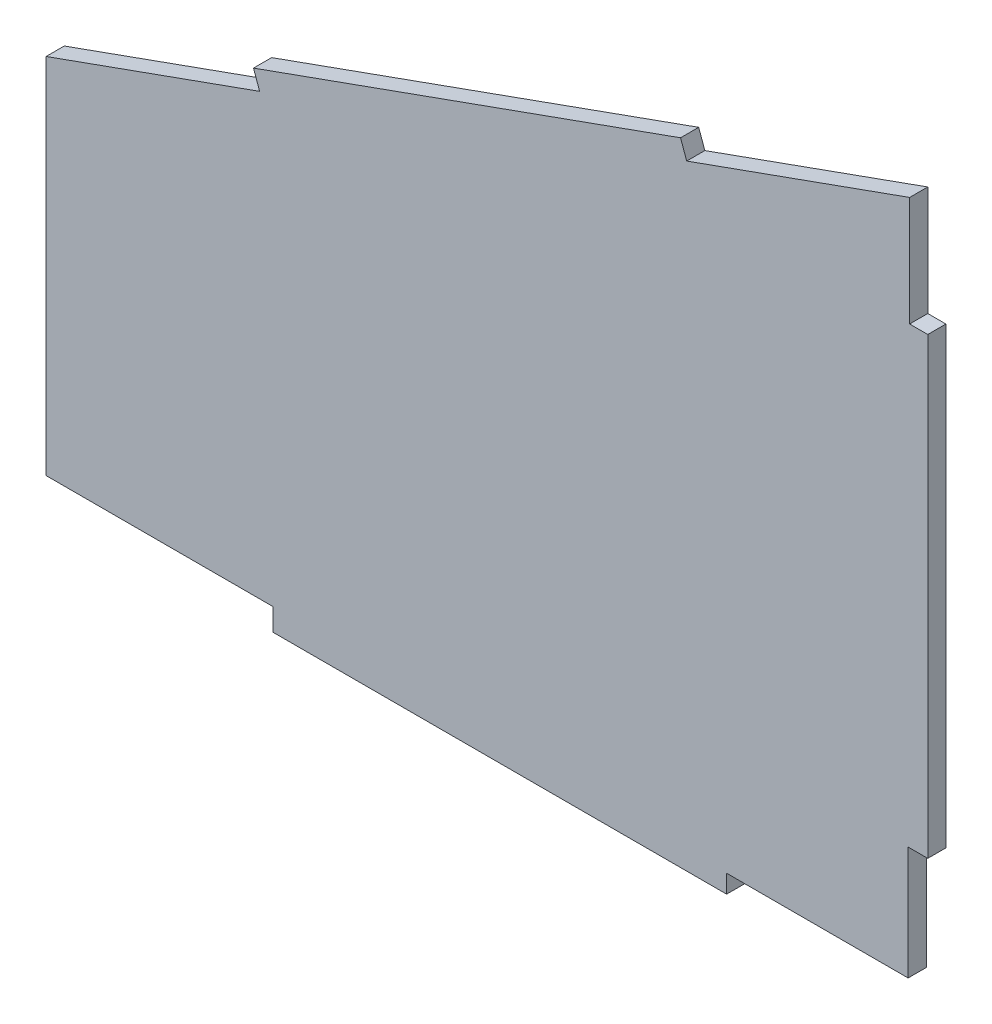
SolidWorks part; units mm, degrees
ref_plane "前视基准面" through (0, 0, 0) normal (0, 0, 1) x (1, 0, 0)
ref_plane "上视基准面" through (0, 0, 0) normal (0, 1, 0) x (1, 0, 0)
ref_plane "右视基准面" through (0, 0, 0) normal (1, 0, 0) x (0, 0, -1)
sketch "草图2" plane through (0, 0, 0) normal (0, 0, 1) x (1, 0, 0)
  line L0 (30.2242, 24.6802) -> (30.2242, 36.7602)
  line L3 (-64.9407, -37.3698) -> (-39.9407, -37.3698)
  line L6 (-64.9407, 2.6302) -> (-64.9407, -37.3698)
  line L8 (-39.9407, -37.3698) -> (-39.9407, -39.8198)
  line L9 (-39.9407, -39.8198) -> (10.0593, -39.8198)
  line L10 (10.0593, -37.8198) -> (10.0593, -39.8198)
  line L13 (30.2242, 24.6802) -> (32.2242, 24.6802)
  line L16 (32.2242, 24.6802) -> (32.2242, -25.3198)
  line L19 (30.2242, 36.7602) -> (5.6564, 27.9492)
  line L29 (-41.4083, 11.0699) -> (-42.0835, 12.9525)
  line L30 (5.6564, 27.9492) -> (4.9812, 29.8318)
  line L31 (-42.0835, 12.9525) -> (4.9812, 29.8318)
  line L33 (10.0593, -37.8198) -> (30.0593, -37.8198)
  line L36 (-41.4083, 11.0699) -> (-64.9407, 2.6302)
  line L43 (30.0593, -37.8198) -> (30.0593, -25.3198)
  line L44 (30.0593, -25.3198) -> (32.2242, -25.3198)
  point P167 (-55.0804, -13.4175)
  point P184 (-14.9407, -38.3698)
  point P197 (41.9196, -11.6019)
  point P204 (-22.6976, 6.5825)
  dimension "D2" = 50
  dimension "D3" = 40
  dimension "D4" = 25
  dimension "D5" = 20
  dimension "D6" = 25
  dimension "D7" = 26.1
  dimension "D8" = 2
  dimension "D9" = 12.5
  dimension "D10" = 2
  dimension "D11" = 2
  dimension "D12" = 12.08
  dimension "D13" = 50
  dimension "D14" = 50
extrude "凸台-拉伸1" add sketch "草图2" along normal blind 2
